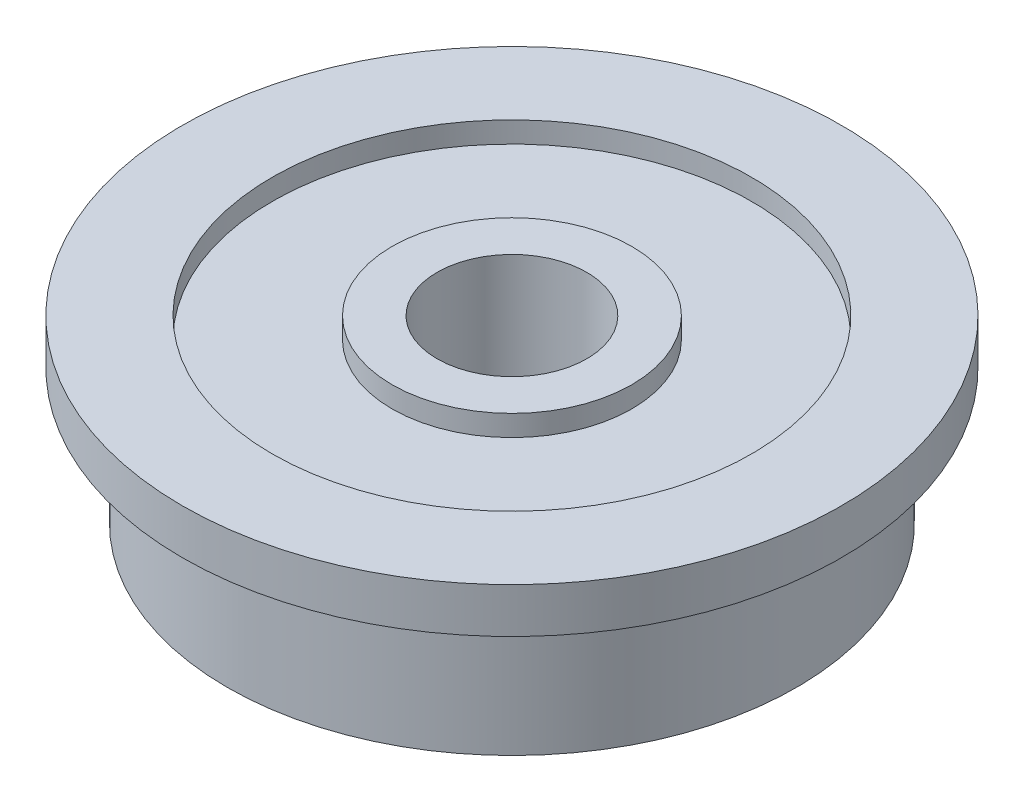
SolidWorks part; units mm, degrees
ref_plane "前视基准面" through (0, 0, 0) normal (0, 0, 1) x (1, 0, 0)
ref_plane "上视基准面" through (0, 0, 0) normal (0, 1, 0) x (1, 0, 0)
ref_plane "右视基准面" through (0, 0, 0) normal (1, 0, 0) x (0, 0, -1)
other "Configuration Table"
sketch "草图1" plane through (0, 0, 0) normal (0, 0, 1) x (1, 0, 0)
  line L0 (0, 4.6113) -> (0, -3.0029) construction
  line L1 (2.5, 6) -> (2.5, 0)
  line L2 (2.5, 0) -> (4, 0)
  line L3 (4, 0) -> (4, 0.7)
  line L4 (4, 0.7) -> (8, 0.7)
  line L5 (8, 0.7) -> (8, 0)
  line L6 (8, 0) -> (9.5, 0)
  line L7 (9.5, 0) -> (9.5, 6)
  line L8 (9.5, 6) -> (8, 6)
  line L9 (8, 6) -> (8, 5.3)
  line L10 (8, 5.3) -> (4, 5.3)
  line L11 (4, 5.3) -> (4, 6)
  line L12 (4, 6) -> (2.5, 6)
  dimension "D1" = 2.5
  dimension "D2" = 9.5
  dimension "D3" = 6
  dimension "D4" = 1.5
  dimension "D5" = 1.5
  dimension "D6" = 0.7
  dimension "D7" = 0.7
revolve "旋转1" add sketch "草图1" angle 360 about L0
fillet "圆角1" [suppressed] radius 0.3
sketch "草图2" plane through (0, 6, 0) normal (0, 1, 0) x (1, 0, 0)
  circle A0 centre (0, 0) radius 9.5
  circle A1 centre (0, 0) radius 11
  dimension "D1" = 22
extrude "凸台-拉伸1" add sketch "草图2" against normal blind 1.5
